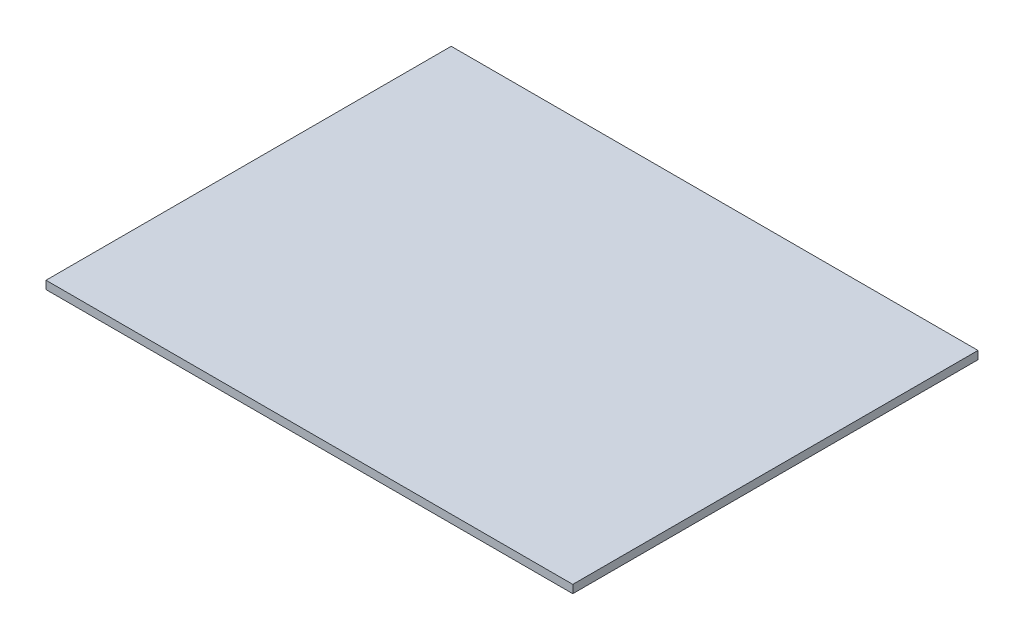
SolidWorks part; units mm, degrees
material "Бальса"
ref_plane "Спереди" through (0, 0, 0) normal (0, 0, 1) x (1, 0, 0)
ref_plane "Сверху" through (0, 0, 0) normal (0, 1, 0) x (1, 0, 0)
ref_plane "Справа" through (0, 0, 0) normal (1, 0, 0) x (0, 0, -1)
sketch "Эскиз1" plane through (0, 0, 0) normal (0, 1, 0) x (1, 0, 0)
  line L1 (0, 0) -> (650, 0)
  line L2 (0, 0) -> (0, 500)
  line L3 (0, 500) -> (650, 500)
  line L4 (650, 0) -> (650, 500)
  dimension "D1" = 650
  dimension "D2" = 500
extrude "Бобышка-Вытянуть1" add sketch "Эскиз1" along normal blind 10
